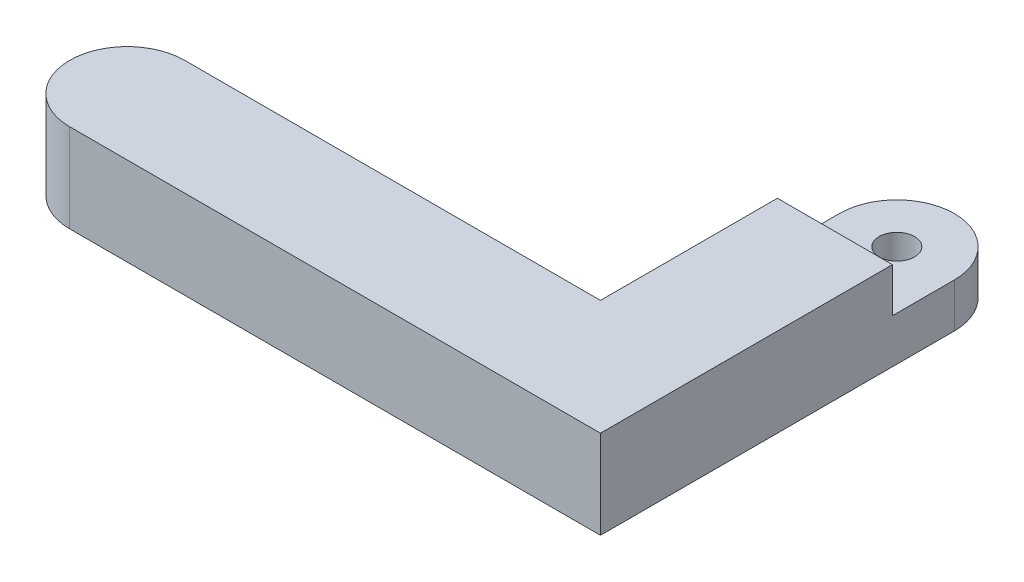
SolidWorks part; units mm, degrees
ref_plane "Alzado" through (0, 0, 0) normal (0, 0, 1) x (1, 0, 0)
ref_plane "Planta" through (0, 0, 0) normal (0, 1, 0) x (1, 0, 0)
ref_plane "Vista lateral" through (0, 0, 0) normal (1, 0, 0) x (0, 0, -1)
sketch "Croquis1" plane through (0, 0, 0) normal (0, 1, 0) x (1, 0, 0)
  line L1 (13, 0) -> (13, -40)
  line L2 (13, -40) -> (-47, -40)
  line L4 (-47, -27) -> (0, -27)
  line L5 (0, -27) -> (0, 0)
  arc A0 (-47, -27) -> (-47, -40) centre (-47, -33.5) ccw
  arc A1 (0, 0) -> (13, 0) centre (6.5, 0) cw
  circle A2 centre (6.5, 0) radius 2
  point P10 (-53.5, -33.5)
  dimension "D2" = 6.5
  dimension "D3" = 6.5
  dimension "D5" = 4
  dimension "D1" = 60
  dimension "D4" = 40
extrude "Saliente-Extruir1" add sketch "Croquis1" along normal blind 10
sketch "Croquis2" plane through (0, 10, 0) normal (0, 1, 0) x (1, 0, 0)
  line L0 (0, 0) -> (0, -7)
  line L1 (0, 0) -> (0, -27) construction
  line L2 (0, -7) -> (13, -7)
  line L3 (13, -40) -> (13, 0) construction
  line L4 (13, -7) -> (13, 0)
  circle A0 centre (6.5, 0) radius 2
  arc A1 (13, 0) -> (0, 0) centre (6.5, 0) ccw
  dimension "D1" = 4
  dimension "D2" = 7
extrude "Cortar-Extruir1" cut sketch "Croquis2" against normal blind 5
